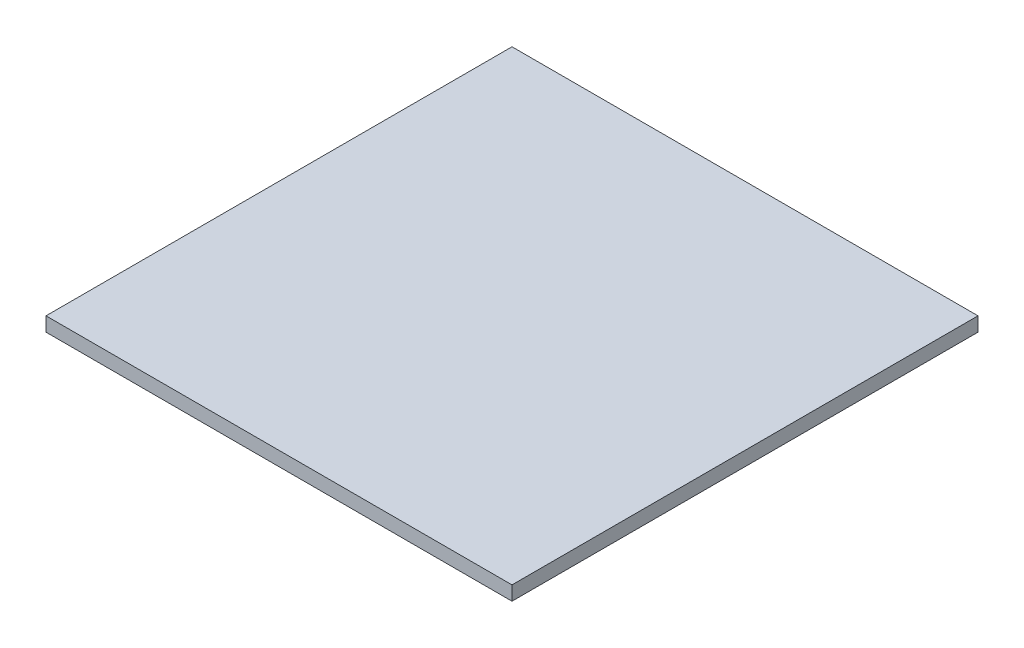
SolidWorks part; units mm, degrees
ref_plane "Front" through (0, 0, 0) normal (0, 0, 1) x (1, 0, 0)
ref_plane "Top" through (0, 0, 0) normal (0, 1, 0) x (1, 0, 0)
ref_plane "Right" through (0, 0, 0) normal (1, 0, 0) x (0, 0, -1)
sketch "Sketch1" plane through (0, 0, 0) normal (0, 1, 0) x (1, 0, 0)
  line L0 (0, 24.9759) -> (0, -607.6565) construction
  line L1 (-263, 0) -> (263, 0)
  line L2 (-263, 0) -> (-263, -526)
  line L3 (-263, -526) -> (263, -526)
  line L4 (263, 0) -> (263, -526)
  dimension "D1" = 526
  dimension "D2" = 526
extrude "Boss-Extrude1" add sketch "Sketch1" along normal blind 16
